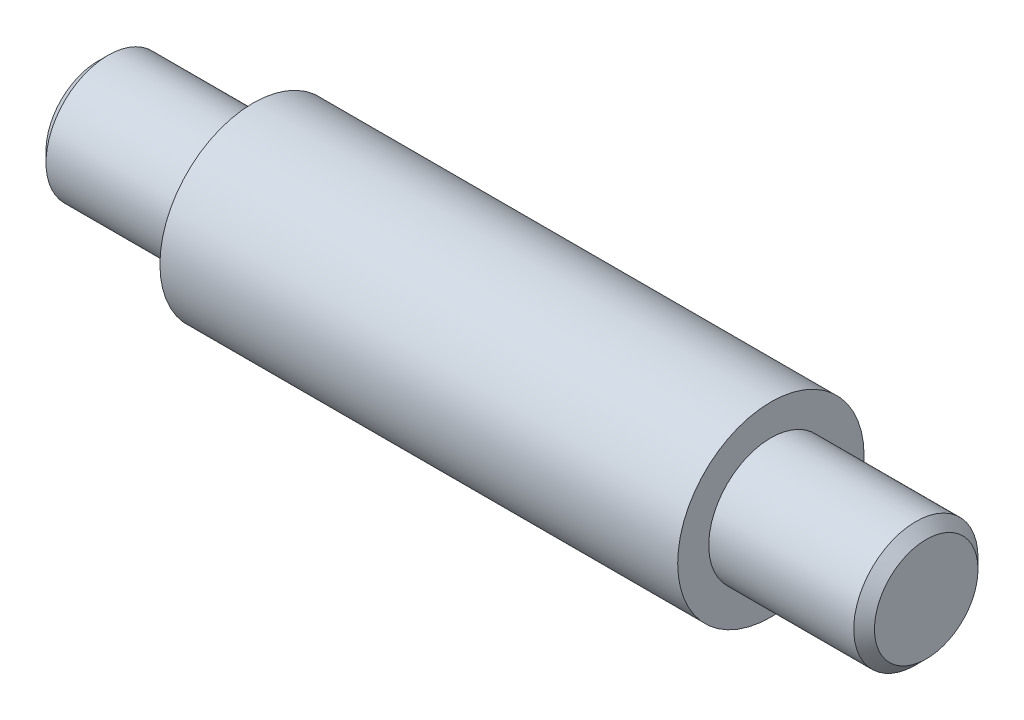
SolidWorks part; units mm, degrees
ref_plane "Front Plane" through (0, 0, 0) normal (0, 0, 1) x (1, 0, 0)
ref_plane "Top Plane" through (0, 0, 0) normal (0, 1, 0) x (1, 0, 0)
ref_plane "Right Plane" through (0, 0, 0) normal (1, 0, 0) x (0, 0, -1)
sketch "Sketch2" plane through (0, 0, 0) normal (0, 0, 1) x (1, 0, 0)
  line L0 (0, 0) -> (0, 5)
  line L1 (1, 6) -> (15, 6)
  line L2 (15, 6) -> (15, 9)
  line L3 (15, 9) -> (65, 9)
  line L4 (65, 9) -> (65, 6)
  line L5 (65, 6) -> (79, 6)
  line L6 (80, 5) -> (80, 0)
  line L7 (80, 0) -> (0, 0)
  line L8 (0, 5) -> (1, 6)
  line L9 (79, 6) -> (80, 5)
  point P1 (0, 6)
  point P8 (80, 6)
revolve "Revolve1" add sketch "Sketch2" angle 360 about L7
